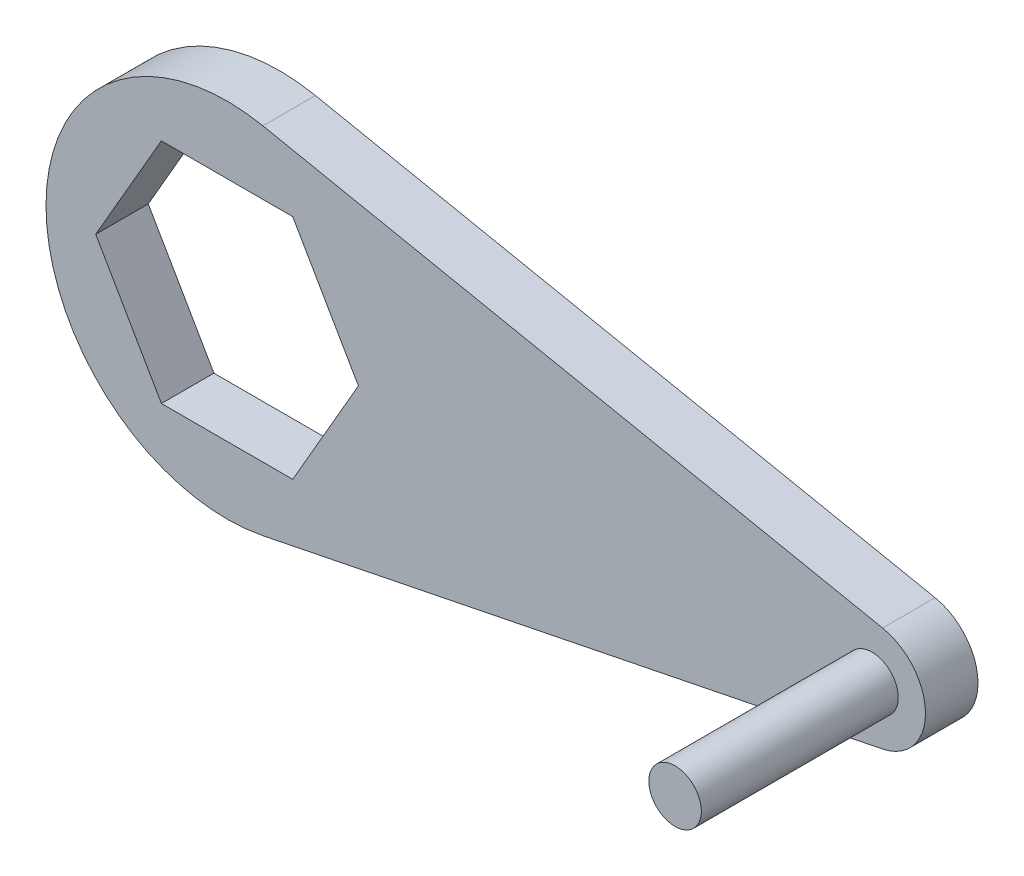
SolidWorks part; units mm, degrees
ref_plane "Front Plane" through (0, 0, 0) normal (0, 0, 1) x (1, 0, 0)
ref_plane "Top Plane" through (0, 0, 0) normal (0, 1, 0) x (1, 0, 0)
ref_plane "Right Plane" through (0, 0, 0) normal (1, 0, 0) x (0, 0, -1)
sketch "Sketch1" plane through (0, 0, 0) normal (0, 0, 1) x (1, 0, 0)
  line L0 (0, 0) -> (63.4085, 0) construction
  line L3 (63.4085, 5.0687) -> (63.4085, -5.0687) construction
  line L4 (12.7036, 0) -> (6.3518, 11.0017)
  line L5 (6.3518, 11.0017) -> (-6.3518, 11.0017)
  line L6 (-6.3518, 11.0017) -> (-12.7036, 0)
  line L7 (-12.7036, 0) -> (-6.3518, -11.0017)
  line L8 (-6.3518, -11.0017) -> (6.3518, -11.0017)
  line L9 (6.3518, -11.0017) -> (12.7036, 0)
  line L10 (3.4652, 17.1677) -> (63.4085, 5.0687)
  line L11 (3.4652, -17.1677) -> (63.4085, -5.0687)
  circle A2 centre (0, 0) radius 11.0017 construction
  arc A3 (3.4652, 17.1677) -> (3.4652, -17.1677) centre (0, 0) ccw
  arc A4 (63.4085, 5.0687) -> (63.4085, -5.0687) centre (62.3854, 0) cw
  point P6 (63.4085, 0)
extrude "Boss-Extrude1" add sketch "Sketch1" along normal blind 5.08 contours L8 L9 L4 L5 L6 L7 | L10 A4 L11 A3
sketch "Sketch2" plane through (0, 0, 5.08) normal (0, 0, 1) x (1, 0, 0)
  circle A0 centre (62.3854, 0) radius 2.54
  arc A1 (63.4085, -5.0687) -> (63.4085, 5.0687) centre (62.3854, 0) ccw construction
  dimension "D1" = 5.08
extrude "Boss-Extrude2" add sketch "Sketch2" along normal blind 19.05
